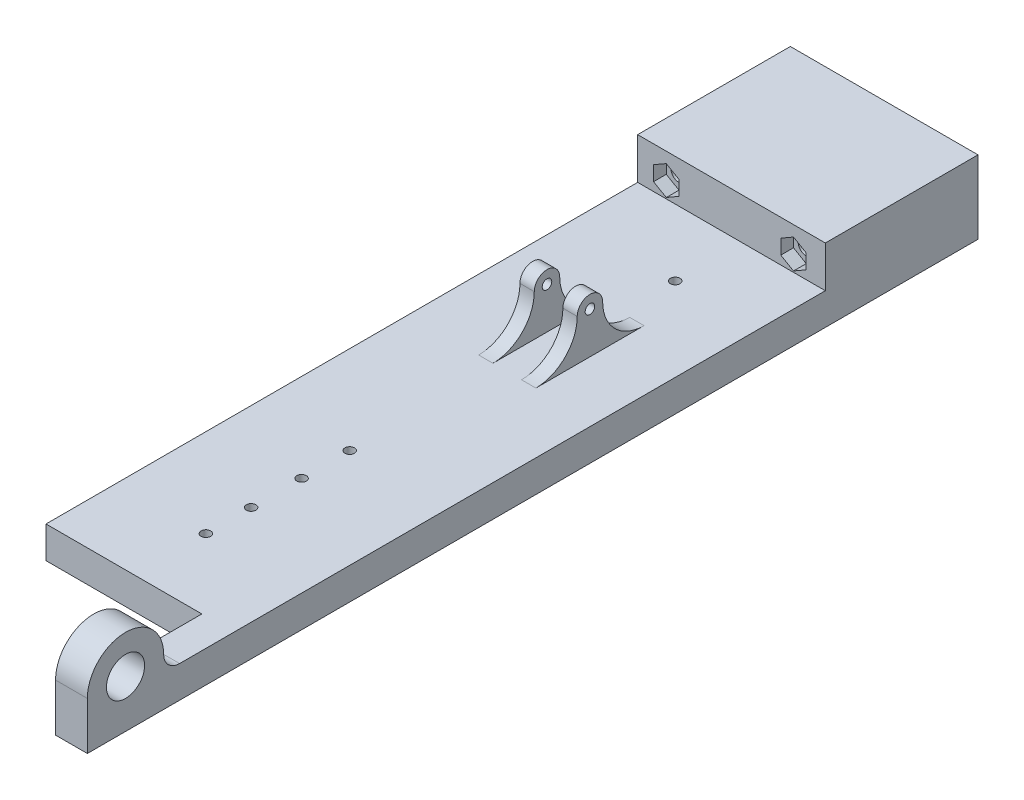
SolidWorks part; units mm, degrees
ref_plane "Front Plane" through (0, 0, 0) normal (0, 0, 1) x (1, 0, 0)
ref_plane "Top Plane" through (0, 0, 0) normal (0, 1, 0) x (1, 0, 0)
ref_plane "Right Plane" through (0, 0, 0) normal (1, 0, 0) x (0, 0, -1)
sketch "Sketch1" plane through (0, 0, 0) normal (1, 0, 0) x (0, 0, -1)
  line L12 (3, 15) -> (3, 0)
  line L13 (3, 0) -> (283, 0)
  line L14 (32, 10) -> (163, 10)
  line L15 (283, 0) -> (283, 23)
  line L18 (197, 10) -> (235, 10)
  line L19 (235, 10) -> (235, 23)
  line L20 (235, 23) -> (283, 23)
  circle A0 centre (15, 15) radius 6
  circle A1 centre (180, 23) radius 1.5
  arc A2 (15, 27) -> (27, 15) centre (15, 15) cw
  arc A3 (15, 27) -> (3, 15) centre (15, 15) ccw
  arc A4 (184, 23) -> (176, 23) centre (180, 23) ccw
  arc A5 (27, 15) -> (32, 10) centre (32, 15) ccw
  arc A6 (176, 23) -> (163, 10) centre (163, 23) cw
  arc A7 (184, 23) -> (197, 10) centre (197, 23) ccw
  dimension "D3" = 12
  dimension "D9" = 3
  dimension "D2" = 280
  dimension "D5" = 12
  dimension "D6" = 5
  dimension "D8" = 10
  dimension "D13" = 13
  dimension "D14" = 4
  dimension "D15" = 48
  dimension "D4" = 15
  dimension "D7" = 12
  dimension "D10" = 165
  dimension "D11" = 8
  dimension "D12" = 131
extrude "Boss-Extrude1" add sketch "Sketch1" along normal blind 59
sketch "Sketch2" plane through (0, 0, 0) normal (0, -1, 0) x (1, 0, 0)
  line L1 (0, -3) -> (49, -3)
  line L2 (0, -3) -> (0, -49)
  line L3 (0, -49) -> (49, -49)
  line L4 (49, -3) -> (49, -49)
  dimension "D1" = 49
  dimension "D2" = 46
extrude "Cut-Extrude1" cut sketch "Sketch2" against normal through all
sketch "Sketch3" plane through (0, 10, 0) normal (0, 1, 0) x (1, 0, 0)
  line L0 (31, 197) -> (31, 147) construction
  line L1 (35.5, 147) -> (26.5, 147)
  line L2 (35.5, 147) -> (35.5, 197)
  line L3 (35.5, 197) -> (26.5, 197)
  line L4 (26.5, 147) -> (26.5, 197)
  line L6 (49, 27) -> (49, 3) construction
  line L8 (0, 197) -> (22, 197)
  line L9 (0, 197) -> (0, 147)
  line L10 (0, 147) -> (22, 147)
  line L11 (22, 197) -> (22, 147)
  line L12 (59, 197) -> (40, 197)
  line L13 (59, 197) -> (59, 147)
  line L14 (59, 147) -> (40, 147)
  line L15 (40, 197) -> (40, 147)
  point P7 (0, 0)
  point P8 (0, 0)
  point P20 (0, 0)
  dimension "D1" = 9
  dimension "D2" = 50
  dimension "D3" = 18
  dimension "D4" = 22
  dimension "D5" = 19
extrude "Cut-Extrude2" cut sketch "Sketch3" along normal through all
sketch "Sketch6" plane through (0, 0, -283) normal (0, 0, -1) x (-1, 0, 0)
  line L0 (-49, 23) -> (-49, 0) construction
  line L2 (-59, 0) -> (-59, 23) construction
  line L16 (-49, 15) -> (0, 15) construction
  line L17 (0, 0) -> (0, 23) construction
  line L18 (-59, 0) -> (0, 0) construction
  line L19 (-49, 10.3812) -> (-45, 12.6906)
  line L20 (-45, 12.6906) -> (-45, 17.3094)
  line L21 (-45, 17.3094) -> (-49, 19.6188)
  line L22 (-49, 19.6188) -> (-53, 17.3094)
  line L23 (-53, 17.3094) -> (-53, 12.6906)
  line L24 (-53, 12.6906) -> (-49, 10.3812)
  line L25 (-9, 10.3812) -> (-5, 12.6906)
  line L26 (-5, 12.6906) -> (-5, 17.3094)
  line L27 (-5, 17.3094) -> (-9, 19.6188)
  line L28 (-9, 19.6188) -> (-13, 17.3094)
  line L29 (-13, 17.3094) -> (-13, 12.6906)
  line L30 (-13, 12.6906) -> (-9, 10.3812)
  circle A0 centre (-49, 15) radius 4 construction
  circle A1 centre (-9, 15) radius 4 construction
  point P13 (-9, 15)
  point P22 (0, 0)
  dimension "D1" = 10
  dimension "D2" = 23
  dimension "D3" = 15
  dimension "D4" = 40
  dimension "D5" = 8
  dimension "D6" = 8
extrude "Cut-Extrude3" cut sketch "Sketch6" against normal blind 4
sketch "Sketch7" plane through (0, 0, -279) normal (0, 0, -1) x (-1, 0, 0)
  line L0 (-49, 19.6188) -> (-49, 10.3812) construction
  line L1 (-9, 19.6188) -> (-9, 10.3812) construction
  circle A0 centre (-49, 15) radius 2.55
  circle A1 centre (-9, 15) radius 2.55
extrude "Cut-Extrude4" cut sketch "Sketch7" against normal blind 82
sketch "Sketch8" plane through (0, 0, -235) normal (0, 0, 1) x (1, 0, 0)
  line L1 (9, 10.3812) -> (13, 12.6906)
  line L2 (13, 12.6906) -> (13, 17.3094)
  line L3 (13, 17.3094) -> (9, 19.6188)
  line L4 (9, 19.6188) -> (5, 17.3094)
  line L5 (5, 17.3094) -> (5, 12.6906)
  line L6 (5, 12.6906) -> (9, 10.3812)
  line L7 (49, 10.3812) -> (53, 12.6906)
  line L8 (53, 12.6906) -> (53, 17.3094)
  line L9 (53, 17.3094) -> (49, 19.6188)
  line L10 (49, 19.6188) -> (45, 17.3094)
  line L11 (45, 17.3094) -> (45, 12.6906)
  line L12 (45, 12.6906) -> (49, 10.3812)
  circle A0 centre (9, 15) radius 4 construction
  circle A1 centre (49, 15) radius 4 construction
extrude "Cut-Extrude5" cut sketch "Sketch8" against normal blind 4
sketch "Sketch9" plane through (0, 10, 0) normal (0, 1, 0) x (1, 0, 0)
  line L0 (27.75, 49) -> (27.75, 235) construction
  line L1 (0, 49) -> (49, 49) construction
  line L2 (59, 235) -> (0, 235) construction
  line L3 (59, 235) -> (59, 32) construction
  line L4 (59, 71.5) -> (0, 71.5) construction
  line L5 (0, 235) -> (0, 49) construction
  line L8 (59, 3) -> (49, 3) construction
  line L9 (32.75, 49) -> (32.75, 235) construction
  line L10 (59, 235) -> (0, 235) construction
  line L11 (27.75, 116.72) -> (59, 116.72) construction
  circle A0 centre (27.75, 71.5) radius 1.5
  circle A1 centre (27.75, 85.74) radius 1.5
  circle A2 centre (27.75, 101.6) radius 1.5
  circle A3 centre (27.75, 116.72) radius 1.5
  circle A4 centre (32.75, 187.78) radius 1.5
  circle A5 centre (32.75, 214.06) radius 1.5
  point P14 (32.75, 116.72)
  point P15 (27.75, 71.5)
  dimension "D3" = 3
  dimension "D5" = 14.24
  dimension "D6" = 3
  dimension "D7" = 3
  dimension "D8" = 3
  dimension "D11" = 3
  dimension "D12" = 3
  dimension "D1" = 31.25
  dimension "D2" = 68.5
  dimension "D4" = 5
  dimension "D9" = 15.86
  dimension "D10" = 15.12
  dimension "D13" = 71.06
  dimension "D14" = 26.28
extrude "Cut-Extrude6" cut sketch "Sketch9" against normal through all
